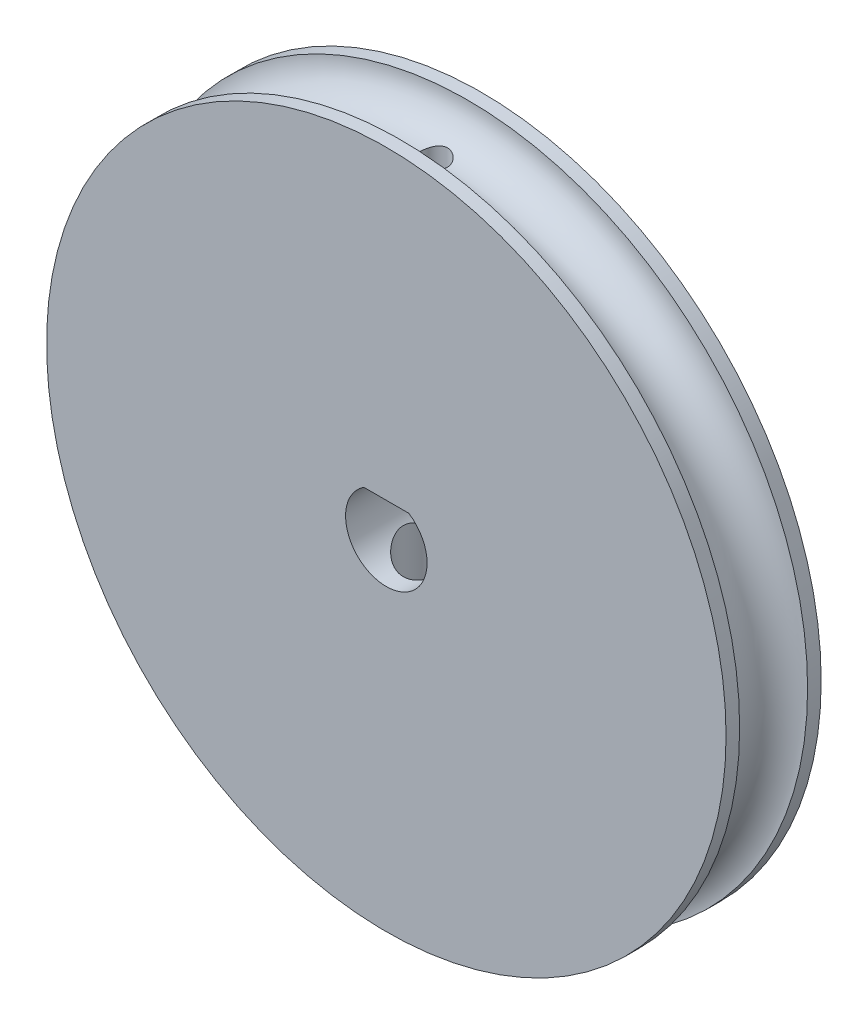
SolidWorks part; units mm, degrees
ref_plane "Front" through (0, 0, 0) normal (0, 0, 1) x (1, 0, 0)
ref_plane "Top" through (0, 0, 0) normal (0, 1, 0) x (1, 0, 0)
ref_plane "Right" through (0, 0, 0) normal (1, 0, 0) x (0, 0, -1)
sketch "Sketch2" plane through (0, 0, 0) normal (0, 1, 0) x (1, 0, 0)
  line L0 (25, 6) -> (25, 7)
  line L1 (0, 0) -> (25, 0)
  line L2 (0, 0) -> (0, 7)
  line L3 (0, 7) -> (25, 7)
  line L4 (25, 0) -> (25, 1)
  arc A0 (25, 6) -> (25, 1) centre (25, 3.5) ccw
  point P6 (0, 0)
  point P9 (0, 0)
  dimension "D3" = 3.5
  dimension "D4" = 5
  dimension "D1" = 7
  dimension "D2" = 25
  dimension "D5" = 3.5
revolve "Revolve1" add sketch "Sketch2" angle 360 about L2
sketch "Sketch3" plane through (0, 0, 0) normal (0, 0, 1) x (1, 0, 0)
  line L0 (-1.6583, 2.5) -> (1.6583, 2.5)
  arc A0 (-1.6583, 2.5) -> (1.6583, 2.5) centre (0, 0) ccw
  dimension "D1" = 6
  dimension "D2" = 2.5
extrude "Cut-Extrude1" cut sketch "Sketch3" against normal through all
sketch "Sketch4" plane through (0, 0, 0) normal (0, 1, 0) x (1, 0, 0)
  circle A0 centre (0, 3.5) radius 1
  dimension "D1" = 2
  dimension "D2" = 3.5
extrude "Cut-Extrude2" cut sketch "Sketch4" against normal through all both and the other way through all
sketch "Sketch6" plane through (0, 0, 0) normal (0, 1, 0) x (1, 0, 0)
  circle A0 centre (0, 3.5) radius 2.25
  dimension "D1" = 4.5
extrude "Cut-Extrude3" cut sketch "Sketch6" against normal through all
